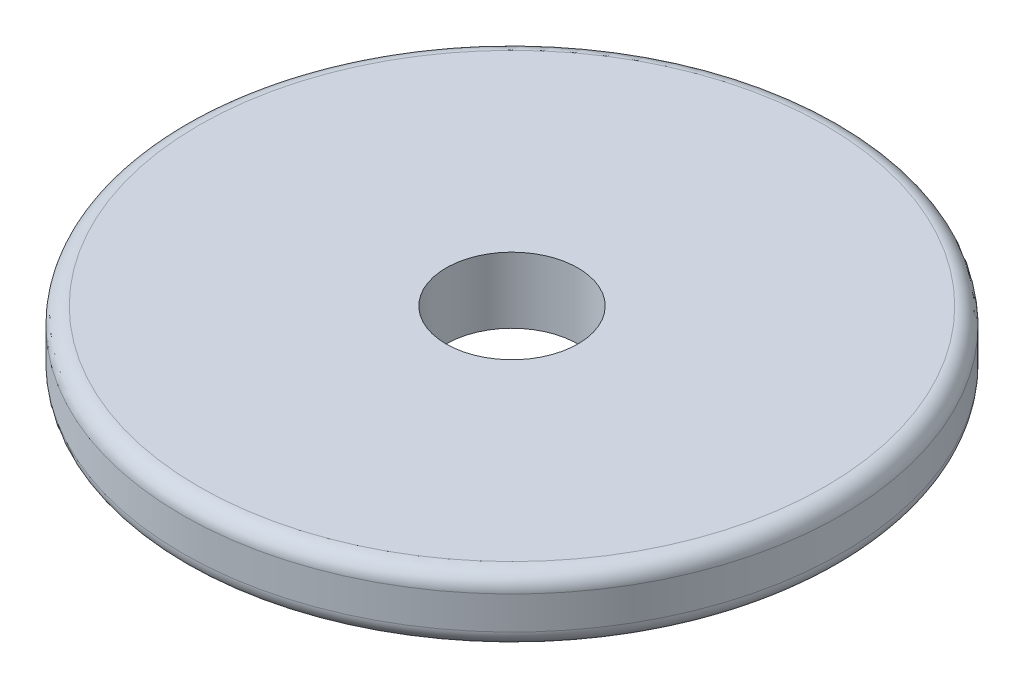
SolidWorks part; units mm, degrees
ref_plane "前视基准面" through (0, 0, 0) normal (0, 0, 1) x (1, 0, 0)
ref_plane "上视基准面" through (0, 0, 0) normal (0, 1, 0) x (1, 0, 0)
ref_plane "右视基准面" through (0, 0, 0) normal (1, 0, 0) x (0, 0, -1)
sketch "草图1" plane through (0, 0, 0) normal (0, 1, 0) x (1, 0, 0)
  circle A0 centre (0, 0) radius 20
  circle A1 centre (0, 0) radius 100
  dimension "D1" = 40
  dimension "D2" = 200
extrude "凸台-拉伸1" add sketch "草图1" along normal blind 20
fillet "圆角1" radius 5 2 edges at (0, 0, 100) (0, 20, 100)
